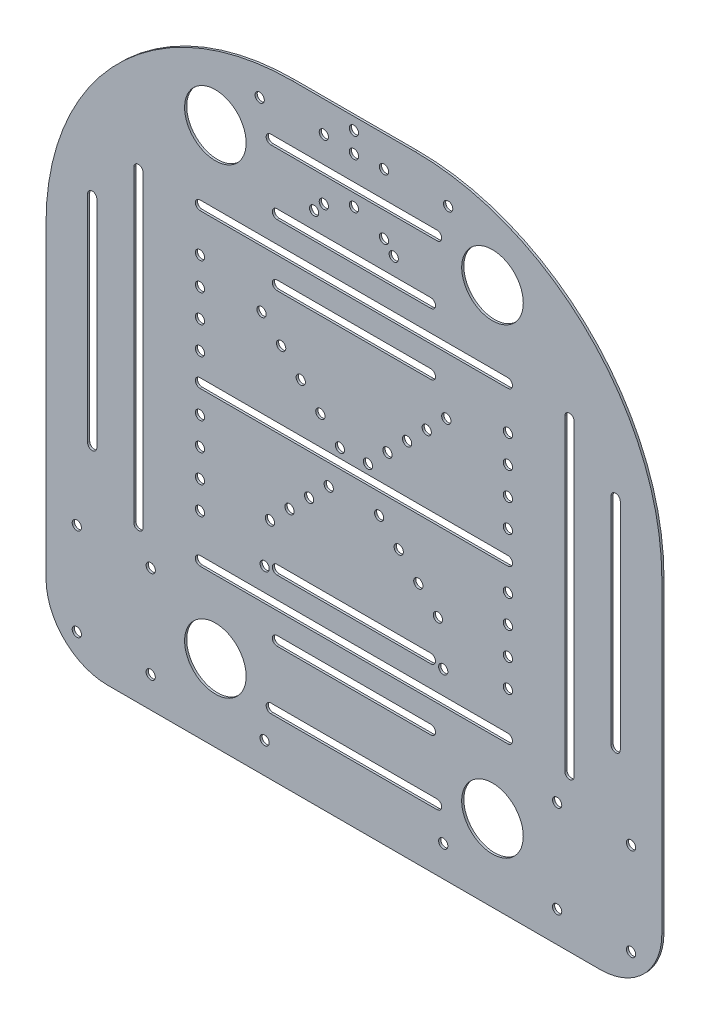
SolidWorks part; units mm, degrees
ref_plane "前视基准面" through (0, 0, 0) normal (0, 0, 1) x (1, 0, 0)
ref_plane "上视基准面" through (0, 0, 0) normal (0, 1, 0) x (1, 0, 0)
ref_plane "右视基准面" through (0, 0, 0) normal (1, 0, 0) x (0, 0, -1)
other "Configuration Table"
sketch "草图1" plane through (0, 0, 0) normal (0, 0, 1) x (1, 0, 0)
  line L0 (0, 0) -> (0, -50000) construction
  line L1 (-20, 100) -> (20, 100)
  line L2 (-100, 20) -> (-100, -80)
  line L3 (-80, -100) -> (80, -100)
  line L4 (100, 20) -> (100, -80)
  line L5 (-100, 100) -> (100, -100) construction
  line L6 (-100, -100) -> (100, 100) construction
  line L7 (0, 0) -> (50000, 0) construction
  line L8 (-50, 50) -> (50, 50) construction
  line L9 (-50, 51.5) -> (50, 51.5)
  line L10 (-50, 48.5) -> (50, 48.5)
  line L11 (-50, -50) -> (50, -50) construction
  line L12 (-50, -51.5) -> (50, -51.5)
  line L13 (-50, -48.5) -> (50, -48.5)
  line L14 (-70, -50) -> (-70, 50) construction
  line L15 (-71.5, -50) -> (-71.5, 50)
  line L16 (-68.5, -50) -> (-68.5, 50)
  line L17 (70, -50) -> (70, 50) construction
  line L18 (71.5, -50) -> (71.5, 50)
  line L19 (68.5, -50) -> (68.5, 50)
  line L20 (-50, 0) -> (50, 0) construction
  line L21 (-50, -1.5) -> (50, -1.5)
  line L22 (-50, 1.5) -> (50, 1.5)
  line L23 (-27, -80) -> (27, -80) construction
  line L24 (-27, -78.5) -> (27, -78.5)
  line L25 (-27, -81.5) -> (27, -81.5)
  line L26 (-27, 80) -> (27, 80) construction
  line L27 (-27, 78.5) -> (27, 78.5)
  line L28 (-27, 81.5) -> (27, 81.5)
  line L29 (-85, 35) -> (-85, -35) construction
  line L30 (-83.5, 35) -> (-83.5, -35)
  line L31 (-86.5, 35) -> (-86.5, -35)
  line L32 (85, 35) -> (85, -35) construction
  line L33 (83.5, 35) -> (83.5, -35)
  line L34 (86.5, 35) -> (86.5, -35)
  line L35 (-25, 40) -> (25, 40) construction
  line L36 (-25, 41.5) -> (25, 41.5)
  line L37 (-25, 38.5) -> (25, 38.5)
  line L38 (-25, 60) -> (25, 60) construction
  line L39 (-25, 61.5) -> (25, 61.5)
  line L40 (-25, 58.5) -> (25, 58.5)
  line L41 (-25, -40) -> (25, -40) construction
  line L42 (-25, -41.5) -> (25, -41.5)
  line L43 (-25, -38.5) -> (25, -38.5)
  line L44 (-25, -60) -> (25, -60) construction
  line L45 (-25, -61.5) -> (25, -61.5)
  line L46 (-25, -58.5) -> (25, -58.5)
  circle A0 centre (-9.77, 90) radius 1.5
  circle A1 centre (9.77, 90) radius 1.5
  circle A2 centre (9.77, 70.46) radius 1.5
  circle A3 centre (-9.77, 70.46) radius 1.5
  arc A4 (100, 20) -> (20, 100) centre (20, 20) ccw
  arc A5 (-20, 100) -> (-100, 20) centre (-20, 20) ccw
  arc A6 (100, -80) -> (80, -100) centre (80, -80) cw
  arc A7 (-80, -100) -> (-100, -80) centre (-80, -80) cw
  circle A8 centre (-90, -60) radius 1.5
  circle A9 centre (-66, -60) radius 1.5
  circle A10 centre (-90, -90) radius 1.5
  circle A11 centre (-66, -90) radius 1.5
  circle A12 centre (66, -90) radius 1.5
  circle A13 centre (66, -60) radius 1.5
  circle A14 centre (90, -90) radius 1.5
  circle A15 centre (90, -60) radius 1.5
  circle A16 centre (29, -41) radius 1.5
  circle A17 centre (29, -90) radius 1.5
  circle A18 centre (-29, -90) radius 1.5
  circle A19 centre (-29, -41) radius 1.5
  arc A20 (-50, 51.5) -> (-50, 48.5) centre (-50, 50) ccw
  arc A21 (50, 48.5) -> (50, 51.5) centre (50, 50) ccw
  arc A22 (-50, -51.5) -> (-50, -48.5) centre (-50, -50) cw
  arc A23 (50, -48.5) -> (50, -51.5) centre (50, -50) cw
  circle A24 centre (-30, 30) radius 1.5
  circle A25 centre (-23.636, 23.636) radius 1.5
  circle A26 centre (-17.2721, 17.2721) radius 1.5
  circle A27 centre (-10.9081, 10.9081) radius 1.5
  circle A28 centre (-4.5442, 4.5442) radius 1.5
  circle A30 centre (8.1838, -8.1838) radius 1.5
  circle A31 centre (14.5477, -14.5477) radius 1.5
  circle A32 centre (20.9117, -20.9117) radius 1.5
  circle A33 centre (27.2756, -27.2756) radius 1.5
  circle A34 centre (30, 30) radius 1.5
  circle A35 centre (23.636, 23.636) radius 1.5
  circle A36 centre (17.2721, 17.2721) radius 1.5
  circle A37 centre (10.9081, 10.9081) radius 1.5
  circle A38 centre (4.5442, 4.5442) radius 1.5
  circle A40 centre (-8.1838, -8.1838) radius 1.5
  circle A41 centre (-14.5477, -14.5477) radius 1.5
  circle A42 centre (-20.9117, -20.9117) radius 1.5
  circle A43 centre (-27.2756, -27.2756) radius 1.5
  arc A44 (-71.5, -50) -> (-68.5, -50) centre (-70, -50) ccw
  arc A45 (-68.5, 50) -> (-71.5, 50) centre (-70, 50) ccw
  arc A46 (71.5, -50) -> (68.5, -50) centre (70, -50) cw
  arc A47 (68.5, 50) -> (71.5, 50) centre (70, 50) cw
  circle A48 centre (-50, 0) radius 1.5
  circle A49 centre (-50, -9) radius 1.5
  circle A50 centre (-50, -18) radius 1.5
  circle A51 centre (-50, -27) radius 1.5
  circle A52 centre (-50, -36) radius 1.5
  circle A53 centre (-50, 9) radius 1.5
  circle A54 centre (-50, 18) radius 1.5
  circle A55 centre (-50, 27) radius 1.5
  circle A56 centre (-50, 36) radius 1.5
  circle A57 centre (50, -36) radius 1.5
  circle A58 centre (50, -27) radius 1.5
  circle A59 centre (50, -18) radius 1.5
  circle A60 centre (50, -9) radius 1.5
  circle A61 centre (50, 36) radius 1.5
  circle A62 centre (50, 27) radius 1.5
  circle A63 centre (50, 18) radius 1.5
  circle A64 centre (50, 9) radius 1.5
  circle A65 centre (50, 0) radius 1.5
  circle A68 centre (-45, 75) radius 10
  circle A69 centre (-45, -75) radius 10
  circle A70 centre (45, -75) radius 10
  circle A71 centre (45, 75) radius 10
  arc A72 (-27, -78.5) -> (-27, -81.5) centre (-27, -80) ccw
  arc A73 (27, -81.5) -> (27, -78.5) centre (27, -80) ccw
  arc A74 (-27, 78.5) -> (-27, 81.5) centre (-27, 80) cw
  arc A75 (27, 81.5) -> (27, 78.5) centre (27, 80) cw
  arc A76 (-83.5, 35) -> (-86.5, 35) centre (-85, 35) ccw
  arc A77 (-86.5, -35) -> (-83.5, -35) centre (-85, -35) ccw
  arc A78 (83.5, 35) -> (86.5, 35) centre (85, 35) cw
  arc A79 (86.5, -35) -> (83.5, -35) centre (85, -35) cw
  circle A80 centre (-1.8198, -1.8198) radius 1.5 [skipped]
  circle A81 centre (1.8198, -1.8198) radius 1.5 [skipped]
  arc A82 (-25, 41.5) -> (-25, 38.5) centre (-25, 40) ccw
  arc A83 (25, 38.5) -> (25, 41.5) centre (25, 40) ccw
  arc A84 (-25, 61.5) -> (-25, 58.5) centre (-25, 60) ccw
  arc A85 (25, 58.5) -> (25, 61.5) centre (25, 60) ccw
  arc A86 (-25, -41.5) -> (-25, -38.5) centre (-25, -40) cw
  arc A87 (25, -38.5) -> (25, -41.5) centre (25, -40) cw
  arc A88 (-25, -61.5) -> (-25, -58.5) centre (-25, -60) cw
  arc A89 (25, -58.5) -> (25, -61.5) centre (25, -60) cw
  point P0 (0, 0)
  point P46 (0, 50)
  point P65 (0, -50)
  point P99 (0, 40)
  point P110 (-70, 0)
  point P119 (70, 0)
  point P160 (0, 0)
  point P175 (0, -80)
  point P183 (0, 80)
  point P189 (-85, 0)
  point P196 (85, 0)
  point P210 (0, 60)
  point P217 (0, -40)
  point P224 (0, -60)
  dimension "D3" = 3
  dimension "D9" = 80
  dimension "D10" = 20
  dimension "D14" = 3
  dimension "D16" = 29
  dimension "D19" = 3
  dimension "D20" = 3
  dimension "D23" = 3
  dimension "D26" = 3
  dimension "D31" = 3
  dimension "D34" = 20
  dimension "D1" = 200
  dimension "D2" = 200
  dimension "D4" = 19.54
  dimension "D5" = 19.54
  dimension "D6" = 19.54
  dimension "D7" = 19.54
  dimension "D8" = 10
  dimension "D11" = 30
  dimension "D12" = 24
  dimension "D13" = 10
  dimension "D15" = 10
  dimension "D17" = 49
  dimension "D18" = 10
  dimension "D21" = 3
  dimension "D22" = 50
  dimension "D24" = 30
  dimension "D28" = 3
  dimension "D29" = 100
  dimension "D30" = 70
  dimension "D35" = 25
  dimension "D36" = 55
  dimension "D37" = 3
  dimension "D38" = 54
  dimension "D39" = 70
  dimension "D40" = 3
  dimension "D41" = 15
  dimension "D42" = 3
  dimension "D43" = 50
  dimension "D44" = 10
  dimension "D45" = 50
  dimension "D46" = 3
  dimension "D47" = 10
  dimension "D25" = 10
  dimension "D27" = 10
  dimension "D32" = 5
  dimension "D33" = 5
extrude "凸台-拉伸1" add sketch "草图1" along normal blind 0.7 contours A7 L3 A6 L4 A4 L1 A5 L2 A77 L31 A76 L30 A73 L25 A72 L24 A69 A68 A63 A61 A59 A57 A56 A55 A54 A53 A52 A51 A50 A49 A45 L16 A44 L15
sketch "草图2" plane through (0, 0, 0.7) normal (0, 0, 1) x (1, 0, 0)
  line L0 (-27, 80) -> (49973, 80) construction
  line L1 (-27, 78.5) -> (27, 78.5) construction
  circle A0 centre (24973, 94.93) radius 1.5
  circle A1 centre (0, 89.43) radius 1.5
  circle A2 centre (12.9298, 67.035) radius 1.5
  circle A3 centre (-12.9298, 67.035) radius 1.5
  circle A4 centre (0, 74.5) radius 1.5
  point P9 (0, 74.5)
  point P12 (-9.77, 90)
  point P18 (-9.77, 70.46)
  point P20 (9.77, 70.46)
  point P22 (9.77, 90)
  dimension "D1" = 3
  dimension "D4" = 3
  dimension "D2" = 3
  dimension "D3" = 14.93
  dimension "D5" = 4
extrude "切除-拉伸1" cut sketch "草图2" against normal blind 40
sketch "草图4" plane through (0, 0, 0.7) normal (0, 0, 1) x (1, 0, 0)
  line L0 (-20, 100) -> (20, 100) construction
  line L1 (0, 0) -> (0, 50000) construction
  circle A0 centre (0, 96) radius 1.5
  circle A1 centre (-30.6085, 90) radius 1.5
  circle A3 centre (30.6085, 90) radius 1.5
  dimension "D1" = 3
  dimension "D4" = 3
  dimension "D2" = 4
  dimension "D3" = 10
extrude "切除-拉伸2" cut sketch "草图4" against normal blind 10
sketch "草图5" plane through (0, 0, 0.7) normal (0, 0, 1) x (1, 0, 0)
  point P0 (-70, 50)
  point P1 (70, 50)
sketch "草图6" plane through (0, 0, 0.7) normal (0, 0, 1) x (1, 0, 0)
  point P0 (-12.9298, 67.035)
  point P1 (0, 74.5)
  point P3 (0, 89.43)
sketch "草图7" plane through (0, 0, 0.7) normal (0, 0, 1) x (1, 0, 0)
  circle A0 centre (-9.77, 70.46) radius 1.5 construction
  circle A1 centre (-9.77, 90) radius 1.5 construction
  point P0 (-8.27, 70.46)
  point P1 (-9.77, 88.5)
  point P4 (-9.77, 91.5)
  point P7 (-9.77, 90)
  point P8 (-9.77, 70.46)
sketch "草图8" plane through (0, 0, 0.7) normal (0, 0, 1) x (1, 0, 0)
  point P0 (-70.088, -49.9689)
  point P1 (-90, -60)
  point P2 (-85, -35)
  point P4 (-66, -60)
  point P6 (-69.7679, -49.9689)
